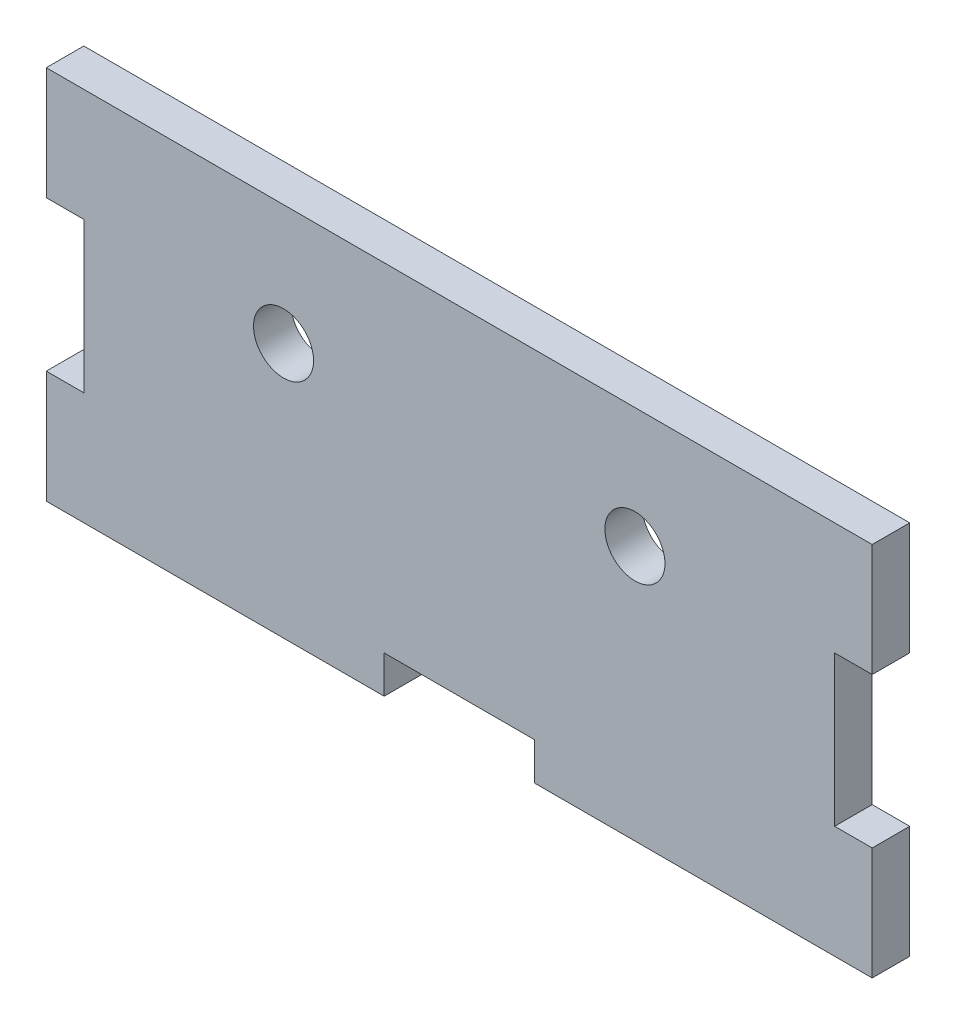
SolidWorks part; units mm, degrees
material "Acrylic (Medium-high impact)"
ref_plane "Front Plane" through (0, 0, 0) normal (0, 0, 1) x (1, 0, 0)
ref_plane "Top Plane" through (0, 0, 0) normal (0, 1, 0) x (1, 0, 0)
ref_plane "Right Plane" through (0, 0, 0) normal (1, 0, 0) x (0, 0, -1)
sketch "Sketch1" plane through (0, 0, 0) normal (0, 0, 1) x (1, 0, 0)
  line L0 (34.925, 31.75) -> (34.925, 0) construction
  line L1 (0, 0) -> (69.85, 0)
  line L2 (0, 0) -> (0, 31.75)
  line L3 (0, 31.75) -> (69.85, 31.75)
  line L4 (69.85, 0) -> (69.85, 31.75)
  line L5 (0, 15.875) -> (69.85, 15.875) construction
  line L6 (0, 22.225) -> (3.175, 22.225)
  line L7 (3.175, 22.225) -> (3.175, 9.525)
  line L8 (0, 9.525) -> (3.175, 9.525)
  line L9 (41.275, 3.175) -> (28.575, 3.175)
  line L10 (28.575, 3.175) -> (28.575, 0)
  line L11 (41.275, 3.175) -> (41.275, 0)
  line L12 (69.85, 9.525) -> (66.675, 9.525)
  line L13 (66.675, 22.225) -> (66.675, 9.525)
  line L14 (69.85, 22.225) -> (66.675, 22.225)
  line L15 (20.066, 21.59) -> (49.784, 21.59) construction
  circle A0 centre (20.066, 21.59) radius 2.54
  circle A1 centre (49.784, 21.59) radius 2.54
  point P14 (3.175, 15.875)
  point P18 (34.925, 3.175)
  dimension "D8" = 5.08
  dimension "D9" = 5.08
  dimension "D1" = 69.85
  dimension "D2" = 31.75
  dimension "D3" = 3.175
  dimension "D4" = 6.35
  dimension "D5" = 6.35
  dimension "D6" = 3.175
  dimension "D7" = 29.718
  dimension "D10" = 10.16
  dimension "D11" = 14.859
extrude "Boss-Extrude1" add sketch "Sketch1" along normal blind 3.175 contours L14 L4 L3 L2 L6 L7 L8 L1 L10 L9 L11 L12 L13 A1 A0
